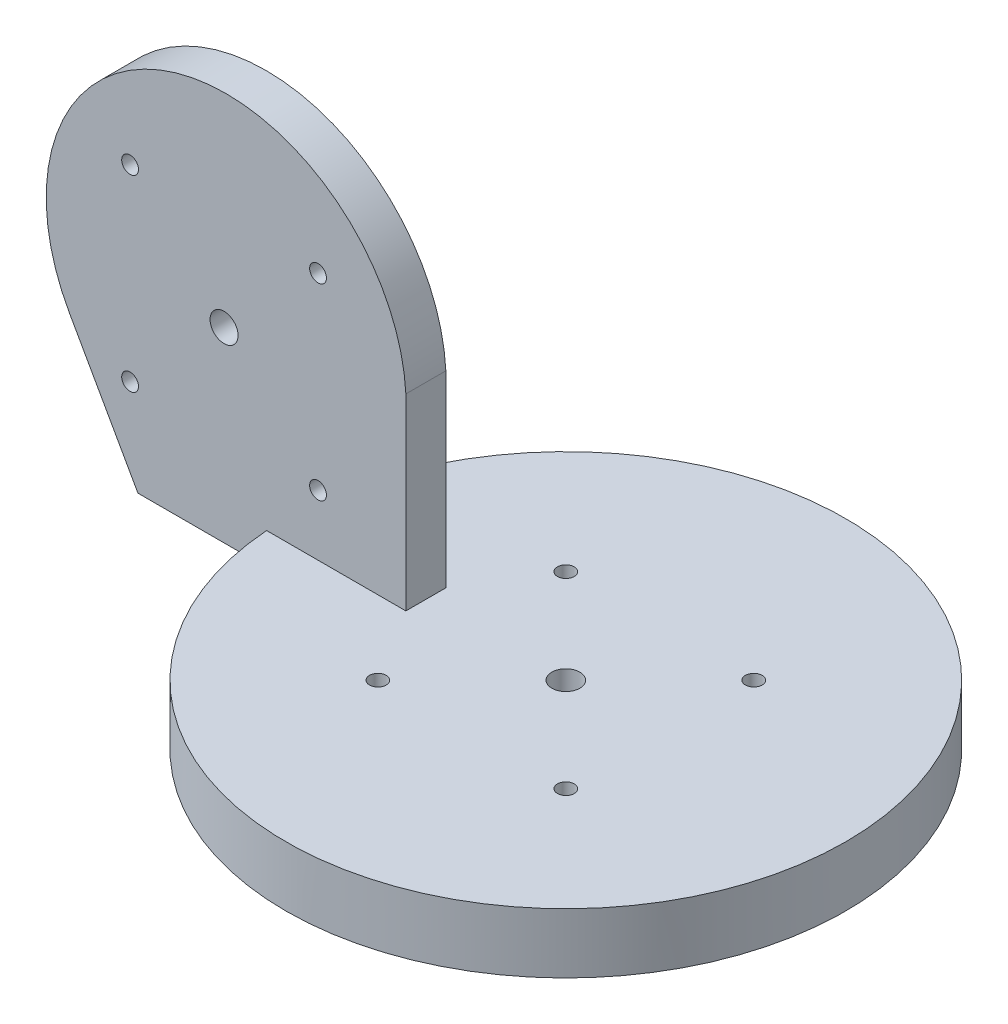
SolidWorks part; units mm, degrees
material "PVC 0.007 Plasticized"
ref_plane "Front Plane" through (0, 0, 0) normal (0, 0, 1) x (1, 0, 0)
ref_plane "Top Plane" through (0, 0, 0) normal (0, 1, 0) x (1, 0, 0)
ref_plane "Right Plane" through (0, 0, 0) normal (1, 0, 0) x (0, 0, -1)
sketch "Sketch1" plane through (0, 0, 0) normal (0, 1, 0) x (1, 0, 0)
  circle A0 centre (0, 0) radius 70
  dimension "D1" = 140
extrude "Boss-Extrude2" add sketch "Sketch1" along normal blind 15 contours A0
sketch "Sketch2" plane through (0, 0, 0) normal (0, -1, 0) x (1, 0, 0)
  circle A0 centre (0, 0) radius 65
  dimension "D1" = 130
extrude "Boss-Extrude3" add sketch "Sketch2" along normal blind 3
sketch "Sketch3" plane through (0, 0, 0) normal (0, 0, 1) x (1, 0, 0)
  line L0 (-35, 62) -> (-35, 7)
  line L1 (-35, 7) -> (-102, 7)
  line L2 (-102, 7) -> (-119.1567, 37.5065)
  arc A0 (-119.1567, 37.5065) -> (-35, 62) centre (-79.9341, 59.5652) cw
  dimension "D5" = 45
  dimension "D1" = 35
  dimension "D2" = 7
  dimension "D3" = 55
  dimension "D4" = 67
  dimension "D6" = 35
extrude "Boss-Extrude4" add sketch "Sketch3" along normal mid plane 10 contours A0 L0 L1 L2
hole_wizard "M5x0.8 Tapped Hole2" positions "Sketch6" profile "Sketch7" tap size "M5x0.8" standard "ANSI Metric"
sketch "Sketch6" plane through (0, 15, 0) normal (0, 1, 0) x (1, 0, 0)
  point P0 (-23.5, 23.5)
  point P2 (23.5, 23.5)
  point P4 (23.5, -23.5)
  point P6 (-23.5, -23.5)
  dimension "D1" = 47
  dimension "D2" = 47
  dimension "D3" = 47
  dimension "D4" = 23.5
  dimension "D5" = 23.5
sketch "Sketch7" plane through (-23.5, 15, -23.5) normal (1, 0, 0) x (0, 0, 1)
  line L0 (0, 0) -> (0, 11.2618)
  line L1 (0, 11.2618) -> (2.1, 10)
  line L2 (2.1, 10) -> (2.1, 0)
  line L5 (2.1, 0) -> (0, 0)
  line L10 (0, 11.2618) -> (-2.1, 10) construction
  line L11 (0, -6.35) -> (0, 107.95) construction
  dimension "Tap Drill Dia." = 4.2
  dimension "Tap Drill Depth" = 10
  dimension "Drill Angle" = 118
cosmetic thread "Hole Thread5" parameters "D1"=10, "D2"=5
cosmetic thread "Hole Thread6" parameters "D1"=10, "D2"=5
cosmetic thread "Hole Thread7" parameters "D1"=10, "D2"=5
cosmetic thread "Hole Thread8" parameters "D1"=10, "D2"=5
sketch "Sketch8" plane through (0, 15, 0) normal (0, 1, 0) x (1, 0, 0)
  circle A0 centre (0, 0) radius 3.5
  dimension "D1" = 7
extrude "Cut-Extrude1" cut sketch "Sketch8" against normal through all
hole_wizard "M5x0.8 Tapped Hole3" positions "Sketch10" profile "Sketch12" tap size "M5x0.8" standard "ANSI Metric"
sketch "Sketch10" plane through (-80.4604, 53.6604, 5) normal (0, 0, 1) x (1, 0, 0)
  point P0 (-23.5, 23.5)
  point P2 (23.5, 23.5)
  point P4 (23.5, -23.5)
  point P6 (-23.5, -23.5)
  dimension "D1" = 47
  dimension "D2" = 47
  dimension "D3" = 47
sketch "Sketch12" plane through (-103.9604, 77.1604, 5) normal (1, 0, 0) x (0, -1, 0)
  line L0 (0, 0) -> (0, 11.2618)
  line L1 (0, 11.2618) -> (2.1, 10)
  line L2 (2.1, 10) -> (2.1, 0)
  line L5 (2.1, 0) -> (0, 0)
  line L10 (0, 11.2618) -> (-2.1, 10) construction
  line L11 (0, -6.35) -> (0, 107.95) construction
  dimension "Tap Drill Dia." = 4.2
  dimension "Tap Drill Depth" = 10
  dimension "Drill Angle" = 118
cosmetic thread "Hole Thread9" parameters "D1"=10, "D2"=5
cosmetic thread "Hole Thread10" parameters "D1"=10, "D2"=5
cosmetic thread "Hole Thread11" parameters "D1"=10, "D2"=5
cosmetic thread "Hole Thread12" parameters "D1"=10, "D2"=5
sketch "Sketch14" plane through (-80.4604, 53.6604, 5) normal (0, 0, 1) x (1, 0, 0)
  circle A0 centre (0, 0) radius 3.5
  dimension "D1" = 7
extrude "Cut-Extrude2" cut sketch "Sketch14" against normal through all
